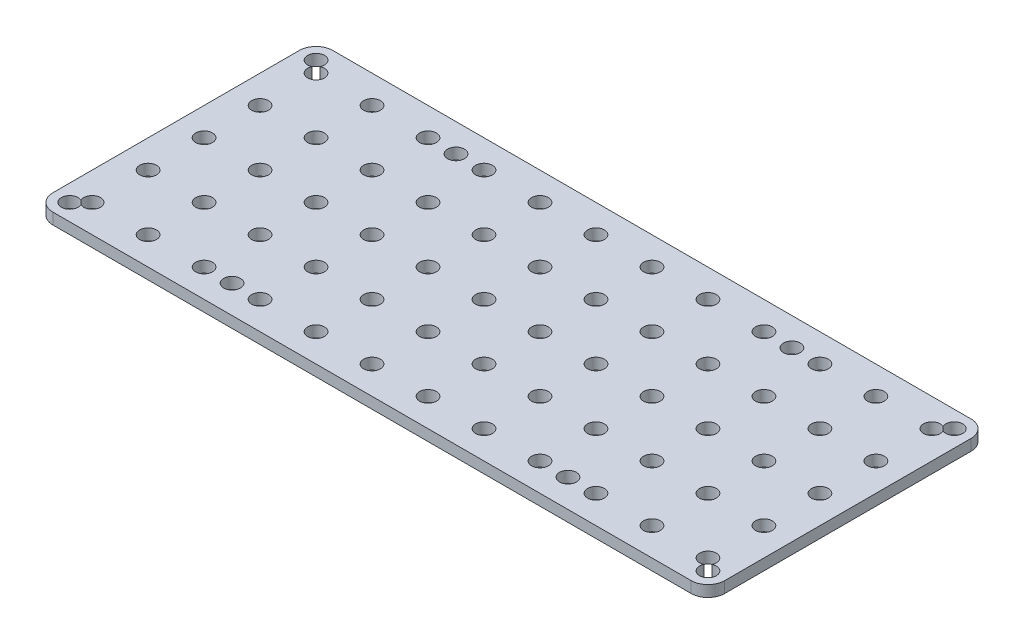
SolidWorks part; units mm, degrees
material "Thornel Mat VMA"
ref_plane "前视基准面" through (0, 0, 0) normal (0, 0, 1) x (1, 0, 0)
ref_plane "上视基准面" through (0, 0, 0) normal (0, 1, 0) x (1, 0, 0)
ref_plane "右视基准面" through (0, 0, 0) normal (1, 0, 0) x (0, 0, -1)
other "Configuration Table"
sketch "草图1" plane through (0, 0, 0) normal (0, 1, 0) x (1, 0, 0)
  line L1 (-60, -25) -> (60, -25)
  line L2 (-60, -25) -> (-60, 25)
  line L3 (-60, 25) -> (60, 25)
  line L4 (60, -25) -> (60, 25)
  line L5 (0, 25) -> (0, -25) construction
  line L6 (-60, 0) -> (60, 0) construction
  point P0 (0, 0)
  dimension "D1" = 120
  dimension "D2" = 50
extrude "凸台-拉伸1" add sketch "草图1" along normal blind 2
sketch "草图2" plane through (0, 2, 0) normal (0, 1, 0) x (1, 0, 0)
  line L0 (-1000, 0) -> (49000, 0) construction
  line L1 (0, -1000) -> (0, 49000) construction
  line L5 (-60, 25) -> (-60, -25) construction
  line L6 (60, 25) -> (-60, 25) construction
  circle A0 centre (-30, 20) radius 1.5
  circle A1 centre (-55, 0) radius 1.5
  circle A2 centre (-30, -20) radius 1.5
  circle A3 centre (30, -20) radius 1.5
  circle A4 centre (55, 0) radius 1.5
  circle A5 centre (30, 20) radius 1.5
  circle A6 centre (-57, 22) radius 1.5
  circle A7 centre (-57, -22) radius 1.5
  circle A8 centre (57, -22) radius 1.5
  circle A9 centre (57, 22) radius 1.5
  dimension "D1" = 55
  dimension "D2" = 3
  dimension "D3" = 3
  dimension "D4" = 30
  dimension "D5" = 20
  dimension "D6" = 3
  dimension "D7" = 3
  dimension "D8" = 3
extrude "切除-拉伸1" cut sketch "草图2" against normal through all
fillet "圆角1" radius 3 4 edges at (-60, 1, 25) (60, 1, 25) (60, 1, -25) (-60, 1, -25)
sketch "草图3" plane through (0, 2, 0) normal (0, 1, 0) x (1, 0, 0)
  circle A112 centre (-55, 20) radius 1.5
  circle A113 centre (-55, 0) radius 1.5 construction
  circle A114 centre (-45, 20) radius 1.5
  circle A115 centre (-35, 20) radius 1.5
  circle A116 centre (-25, 20) radius 1.5
  circle A117 centre (-15, 20) radius 1.5
  circle A118 centre (-5, 20) radius 1.5
  circle A119 centre (5, 20) radius 1.5
  circle A120 centre (15, 20) radius 1.5
  circle A121 centre (25, 20) radius 1.5
  circle A122 centre (35, 20) radius 1.5
  circle A123 centre (45, 20) radius 1.5
  circle A124 centre (55, 20) radius 1.5
  circle A125 centre (-45, 10) radius 1.5
  circle A126 centre (-35, 10) radius 1.5
  circle A127 centre (-25, 10) radius 1.5
  circle A128 centre (-15, 10) radius 1.5
  circle A129 centre (-5, 10) radius 1.5
  circle A130 centre (5, 10) radius 1.5
  circle A131 centre (15, 10) radius 1.5
  circle A132 centre (25, 10) radius 1.5
  circle A133 centre (35, 10) radius 1.5
  circle A134 centre (45, 10) radius 1.5
  circle A135 centre (55, 10) radius 1.5
  circle A136 centre (-45, 0) radius 1.5
  circle A137 centre (-35, 0) radius 1.5
  circle A138 centre (-25, 0) radius 1.5
  circle A139 centre (-15, 0) radius 1.5
  circle A140 centre (-5, 0) radius 1.5
  circle A141 centre (5, 0) radius 1.5
  circle A142 centre (15, 0) radius 1.5
  circle A143 centre (25, 0) radius 1.5
  circle A144 centre (35, 0) radius 1.5
  circle A145 centre (45, 0) radius 1.5
  circle A146 centre (55, 0) radius 1.5
  circle A147 centre (-45, -10) radius 1.5
  circle A148 centre (-35, -10) radius 1.5
  circle A149 centre (-25, -10) radius 1.5
  circle A150 centre (-15, -10) radius 1.5
  circle A151 centre (-5, -10) radius 1.5
  circle A152 centre (5, -10) radius 1.5
  circle A153 centre (15, -10) radius 1.5
  circle A154 centre (25, -10) radius 1.5
  circle A155 centre (35, -10) radius 1.5
  circle A156 centre (45, -10) radius 1.5
  circle A157 centre (55, -10) radius 1.5
  circle A158 centre (-45, -20) radius 1.5
  circle A159 centre (-35, -20) radius 1.5
  circle A160 centre (-25, -20) radius 1.5
  circle A161 centre (-15, -20) radius 1.5
  circle A162 centre (-5, -20) radius 1.5
  circle A163 centre (5, -20) radius 1.5
  circle A164 centre (15, -20) radius 1.5
  circle A165 centre (25, -20) radius 1.5
  circle A166 centre (35, -20) radius 1.5
  circle A167 centre (45, -20) radius 1.5
  circle A168 centre (55, -20) radius 1.5
  circle A169 centre (-55, 10) radius 1.5
  circle A170 centre (-55, 0) radius 1.5
  circle A171 centre (-55, -10) radius 1.5
  circle A172 centre (-55, -20) radius 1.5
  dimension "D1" = 3
  dimension "D2" = 20
  dimension "D3" = 55
extrude "切除-拉伸2" cut sketch "草图3" against normal through all
